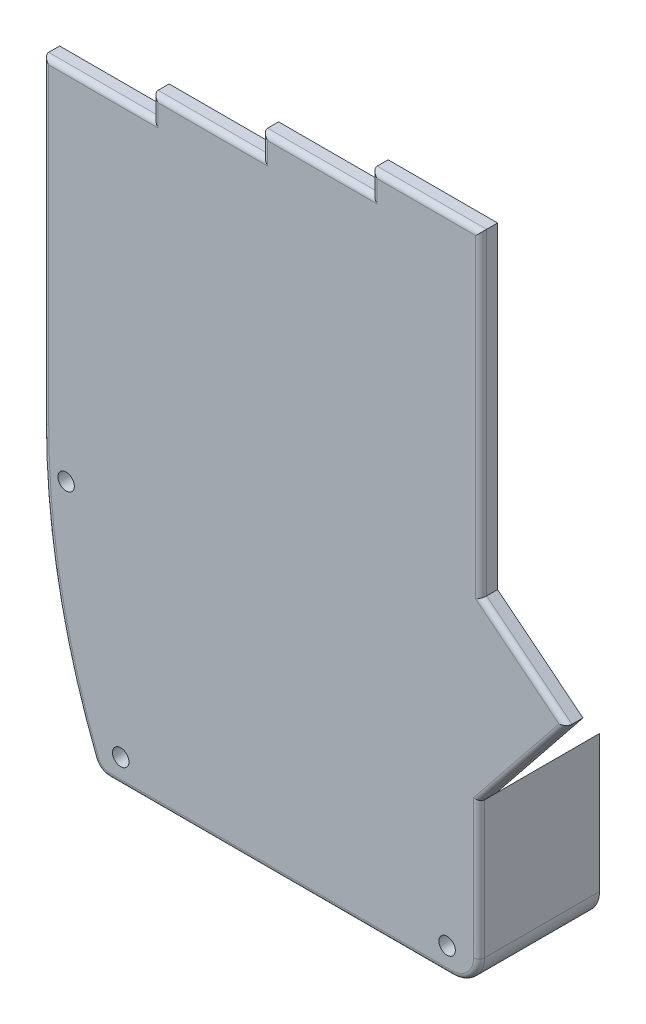
SolidWorks part; units mm, degrees
ref_plane "Front Plane" through (0, 0, 0) normal (0, 0, 1) x (1, 0, 0)
ref_plane "Top Plane" through (0, 0, 0) normal (0, 1, 0) x (1, 0, 0)
ref_plane "Right Plane" through (0, 0, 0) normal (1, 0, 0) x (0, 0, -1)
sketch "Sketch1" plane through (0, 0, 0) normal (0, 0, 1) x (1, 0, 0)
  line L0 (0.0888, 50.4455) -> (0.0888, 108.4455)
  line L26 (45.0813, 0) -> (12.0902, 0)
  line L59 (0.0888, 108.4455) -> (20.0888, 108.4455)
  line L60 (20.0888, 108.4455) -> (20.0888, 112.4455)
  line L61 (20.0888, 112.4455) -> (40.0888, 112.4455)
  line L62 (40.0888, 112.4455) -> (40.0888, 116.4455)
  line L63 (40.0888, 116.4455) -> (60.0888, 116.4455)
  line L64 (60.0888, 116.4455) -> (60.0888, 120.4455)
  line L68 (60.0888, 120.4455) -> (80.0888, 120.4455)
  line L70 (74.72, 0) -> (45.0813, 0)
  line L72 (80.0888, 62.4455) -> (80.0888, 120.4455)
  line L73 (80.0888, 62.4455) -> (95.6967, 49.9398)
  line L75 (95.6967, 49.9398) -> (79.72, 30)
  line L77 (79.72, 30) -> (79.72, 5)
  arc A1 (0.0888, 50.4455) -> (9.2995, 1.8991) centre (132.1238, 50.3497) ccw
  arc A2 (12.0902, 0) -> (9.2995, 1.8991) centre (12.0902, 3) cw
  arc A3 (79.72, 5) -> (74.72, 0) centre (74.72, 5) cw
  point P19 (79.72, 0)
  dimension "D3" = 20
  dimension "D6" = 50.4455
  dimension "D1" = 58
  dimension "D9" = 3
  dimension "D10" = 4
  dimension "D2" = 58
  dimension "D4" = 30
  dimension "D5" = 32.4455
  dimension "D7" = 70.4205
  dimension "D8" = 80
  dimension "D11" = 4
  dimension "D12" = 4
  dimension "D13" = 20
  dimension "D14" = 20
  dimension "D15" = 20
extrude "Boss-Extrude1" add sketch "Sketch1" against normal blind 3
sketch "Sketch19" plane through (0, 0, 0) normal (0, 0, 1) x (1, 0, 0)
  line L0 (45.0813, 0) -> (12.0902, 0)
  line L1 (11.2449, 8.0001) -> (18.2449, 8.0001)
  line L2 (18.2449, 8.0001) -> (18.2449, 2.9841)
  line L3 (76.8742, 7.9841) -> (69.8742, 7.9841)
  line L4 (74.72, 0) -> (45.0813, 0)
  line L5 (79.72, 30) -> (79.72, 5)
  line L6 (79.72, 5) -> (79.72, 30) construction
  line L7 (95.6967, 49.9398) -> (79.72, 30) construction
  line L8 (69.8742, 7.9841) -> (69.8742, 2.9841)
  line L9 (3.269, 46.1327) -> (7.269, 46.1327)
  line L10 (7.269, 46.1327) -> (7.269, 41.1327)
  line L13 (7.269, 41.1327) -> (3.8109, 39.6114)
  line L14 (45.2355, 2.9841) -> (18.2449, 2.9841)
  line L15 (69.8742, 2.9841) -> (45.2355, 2.9841)
  line L16 (76.9333, 26.522) -> (76.8742, 7.9841)
  line L17 (0.0888, 50.4455) -> (3.0888, 50.4455)
  line L18 (76.9333, 26.522) -> (79.72, 30)
  arc A0 (3.8109, 39.6114) -> (11.2449, 8.0001) centre (135.0811, 53.8023) ccw
  arc A3 (0.0888, 50.4455) -> (9.2995, 1.8991) centre (132.1238, 50.3497) ccw
  arc A4 (12.0902, 0) -> (9.2995, 1.8991) centre (12.0902, 3) cw
  arc A5 (79.72, 5) -> (74.72, 0) centre (74.72, 5) cw
  arc A12 (3.0888, 50.4455) -> (3.269, 46.1327) centre (135.0811, 53.8023) ccw
  dimension "D1" = 7
  dimension "D2" = 7
  dimension "D3" = 5
  dimension "D4" = 4
  dimension "D5" = 5
extrude "Boss-Extrude6" add sketch "Sketch19" against normal blind 22
sketch "Sketch23" plane through (0, 0, -22) normal (0, 0, -1) x (-1, 0, 0)
  line L1 (-18.2449, 2.9841) -> (-18.2449, 8.0001) construction
  line L2 (-18.2449, 8.0001) -> (-11.2449, 8.0001) construction
  line L3 (-69.8742, 7.9841) -> (-69.8742, 2.9841) construction
  line L4 (-76.8742, 7.9841) -> (-69.8742, 7.9841) construction
  circle A0 centre (-4.269, 43.1327) radius 1.5
  circle A1 centre (-14.2449, 4.5001) radius 1.5
  circle A2 centre (-73.8742, 4.4841) radius 1.5
  dimension "D1" = 3
  dimension "D5" = 3
  dimension "D3" = 4
  dimension "D4" = 3.5
  dimension "D6" = 4
  dimension "D7" = 3.5
extrude "Cut-Extrude2" cut sketch "Sketch23" against normal up to next
fillet "Fillet2" radius 1 16 edges at (20.0888, 110.4455, 0) (40.0888, 114.4455, 0) (60.0888, 118.4455, 0) (70.0888, 120.4455, 0) (50.0888, 116.4455, 0) (30.0888, 112.4455, 0) (10.0888, 108.4455, 0) (0.0888, 79.4455, 0) (80.0888, 91.4455, 0) (87.8927, 56.1926, 0) (87.7083, 39.9699, 0) (79.72, 17.5, 0) (78.2555, 1.4645, 0) (10.4024, 0.5198, 0) (2.4029, 25.7376, 0) (43.4051, 0, 0)
sketch "Sketch26" plane through (0, 0, 0) normal (0, -1, 0) x (1, 0, 0)
  line L1 (12.0902, -1) -> (74.72, -1)
  line L2 (12.0902, -1) -> (12.0902, -22)
  line L3 (12.0902, -22) -> (74.72, -22)
  line L4 (74.72, -1) -> (74.72, -22)
extrude "Boss-Extrude8" add sketch "Sketch26" along normal blind 0.1
sketch "Sketch28" plane through (0, 2.9841, 0) normal (0, 1, 0) x (1, 0, 0)
  line L0 (69.8742, 22) -> (18.2449, 22) construction
  circle A0 centre (44.0596, 12.5) radius 7
  point P2 (0, 0)
  dimension "D1" = 14
  dimension "D2" = 9.5
extrude "Cut-Extrude4" cut sketch "Sketch28" against normal up to next
